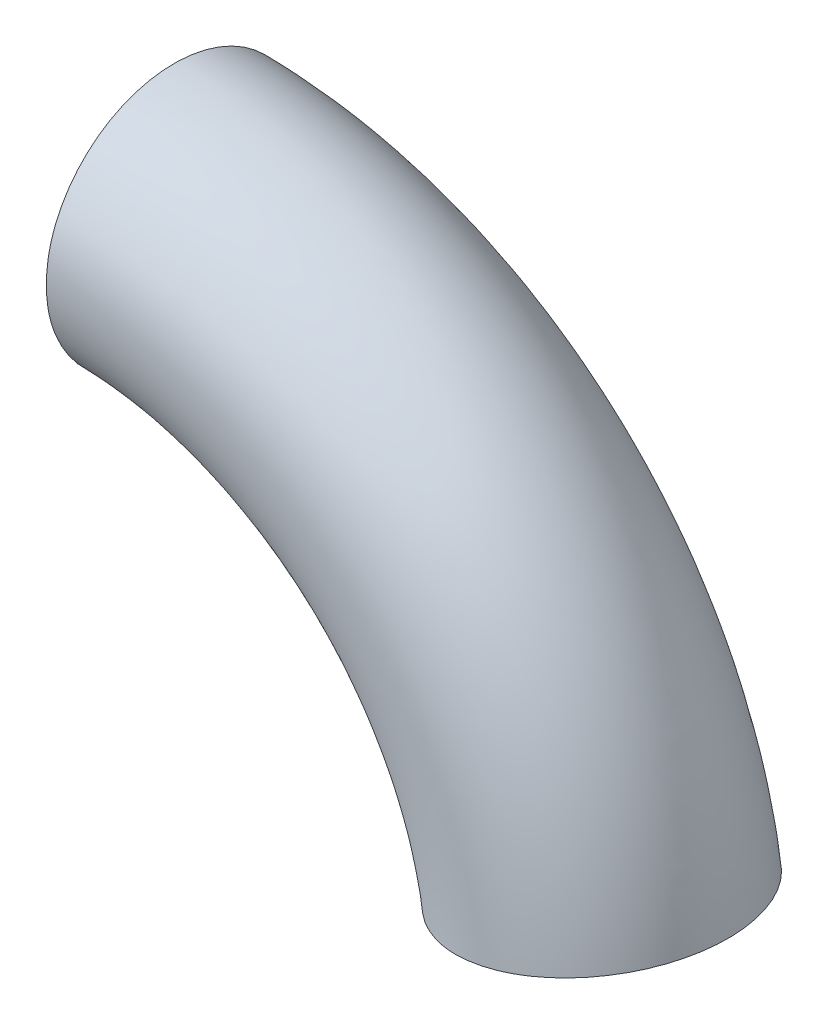
SolidWorks part; units mm, degrees
ref_plane "Front Plane" through (0, 0, 0) normal (0, 0, 1) x (1, 0, 0)
ref_plane "Top Plane" through (0, 0, 0) normal (0, 1, 0) x (1, 0, 0)
ref_plane "Right Plane" through (0, 0, 0) normal (1, 0, 0) x (0, 0, -1)
sketch "Sketch1" plane through (0, 0, 0) normal (1, 0, 0) x (0, 0, -1)
  circle A0 centre (0, 0) radius 50
  circle A1 centre (0, 0) radius 52.5
  dimension "D1" = 100
  dimension "D2" = 105
sketch "Sketch4" plane through (0, 0, 0) normal (0, 0, 1) x (1, 0, 0)
  arc A0 (0, 0) -> (175.6141, -153.3482) centre (-2.4043, -179.9839) cw
  dimension "D1" = 180
sweep "Sweep7" add profiles "Sketch1" path "Sketch4"
